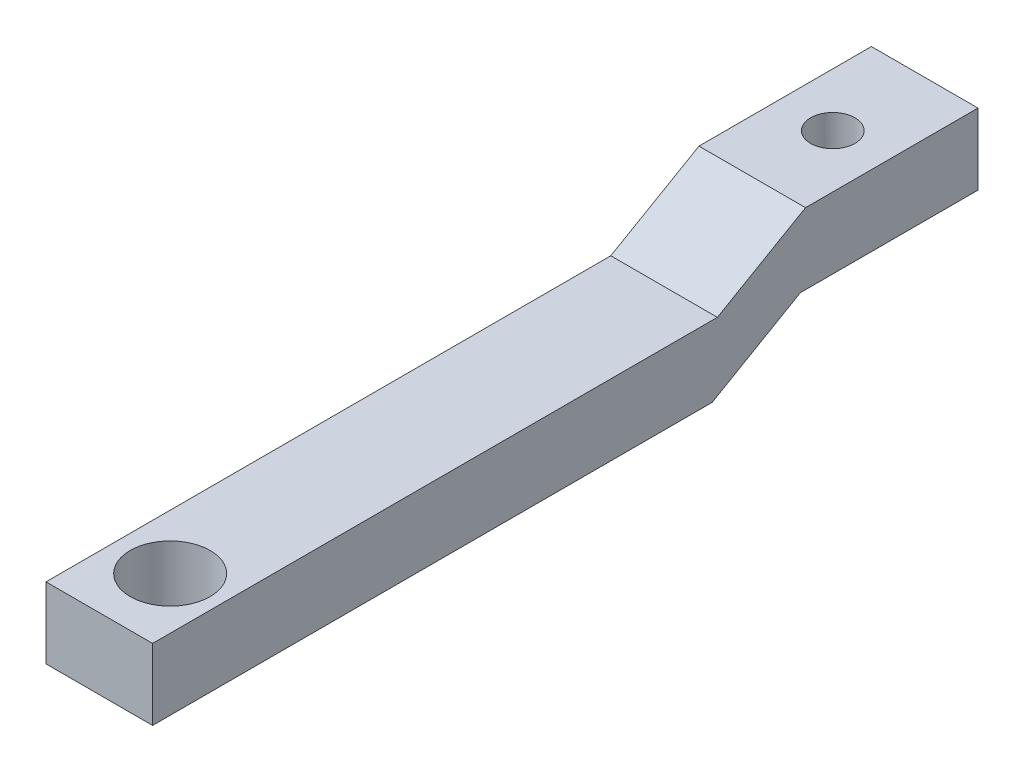
SolidWorks part; units mm, degrees
material "Copper"
ref_plane "Front Plane" through (0, 0, 0) normal (0, 0, 1) x (1, 0, 0)
ref_plane "Top Plane" through (0, 0, 0) normal (0, 1, 0) x (1, 0, 0)
ref_plane "Right Plane" through (0, 0, 0) normal (1, 0, 0) x (0, 0, -1)
sketch "Sketch1" plane through (0, 0, 0) normal (1, 0, 0) x (0, 0, -1)
  line L1 (72.92, 0) -> (92.92, 0)
  line L3 (73.5046, 8) -> (92.92, 8)
  line L4 (92.92, 0) -> (92.92, 8)
  line L5 (0, 55) -> (0, -55) construction
  line L6 (0, 0) -> (0, 2.27)
  line L7 (0, -5.73) -> (26.973, -5.73)
  line L8 (0, 2.27) -> (63.5799, 2.27)
  line L9 (92.92, 3.3148) -> (92.92, 0)
  line L10 (62.9953, -5.73) -> (26.973, -5.73)
  line L11 (72.92, 0) -> (62.9953, -5.73)
  line L12 (73.5046, 8) -> (63.5799, 2.27)
  line L13 (72.92, 0) -> (92.92, 0)
  line L14 (0, 2.27) -> (0, -5.73)
  dimension "D1" = 150
  dimension "D2" = 150
  dimension "D3" = 8
  dimension "D4" = 8
  dimension "D5" = 20
  dimension "D6" = 92.92
  dimension "D7" = 5.73
extrude "Boss-Extrude1" add sketch "Sketch1" against normal blind 12 contours L6 L14 L7 L10 L11 L1 L4 L3 L12 L8
sketch "Sketch2" plane through (0, 8, 0) normal (0, 1, 0) x (1, 0, 0)
  line L0 (-5.808, 0) -> (-6, 92.92) construction
  line L1 (-55, 0) -> (55, 0) construction
  line L2 (-12, 92.92) -> (0, 92.92) construction
  circle A0 centre (-5.8241, 7.8) radius 4.5
  circle A1 centre (-5.9786, 82.55) radius 2.5
  point P10 (0, 0)
  dimension "D1" = 10.37
  dimension "D2" = 7.8
extrude "Cut-Extrude1" cut sketch "Sketch2" along direction (0, -1, 0) on the side against the normal up to next (13.73 mm away) contours L0 A0 | A0 L0 | L0 A1 | A1 L0
